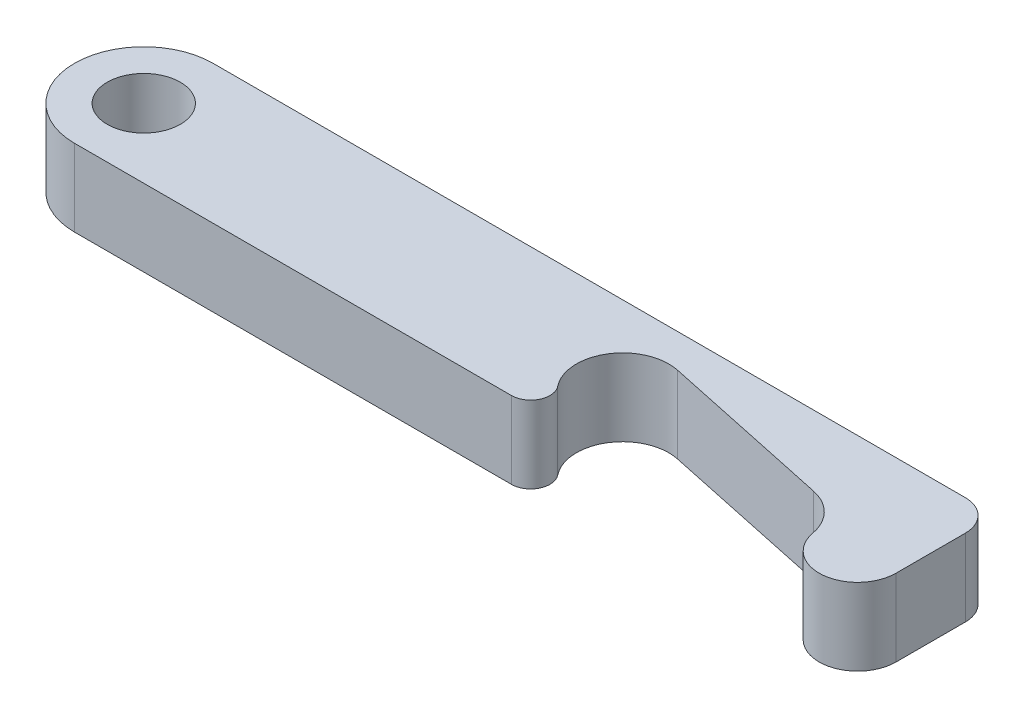
SolidWorks part; units mm, degrees
ref_plane "Front Plane" through (0, 0, 0) normal (0, 0, 1) x (1, 0, 0)
ref_plane "Top Plane" through (0, 0, 0) normal (0, 1, 0) x (1, 0, 0)
ref_plane "Right Plane" through (0, 0, 0) normal (1, 0, 0) x (0, 0, -1)
sketch "Sketch1" plane through (0, 0, 0) normal (0, 1, 0) x (1, 0, 0)
  line L0 (-50.5, 9) -> (47.2578, 9)
  line L1 (51.2578, 5) -> (51.2578, -4)
  line L2 (6.282, -9) -> (-50.5, -9)
  line L4 (14.1887, 4.6514) -> (36.6887, -0.1311)
  arc A0 (51.2578, 5) -> (47.2578, 9) centre (47.2578, 5) ccw
  arc A1 (46.2578, -9) -> (51.2578, -4) centre (46.2578, -4) ccw
  arc A2 (-50.5, 9) -> (-50.5, -9) centre (-50.5, 0) ccw
  circle A3 centre (-50.5, 0) radius 4.75
  arc A4 (14.1887, 4.6514) -> (8.2406, -4.9463) centre (12.9412, -1.2175) ccw
  arc A5 (41.3412, -4.9091) -> (36.6887, -0.1311) centre (35.4412, -6) ccw
  arc A6 (41.3412, -4.9091) -> (51.2578, -4) centre (46.2578, -4) ccw
  arc A7 (6.282, -9) -> (8.2406, -4.9463) centre (6.282, -6.5) ccw
  point P22 (-59.5, 0)
  dimension "D2" = 8
  dimension "D3" = 10
  dimension "D4" = 9.5
  dimension "D5" = 12
  dimension "D6" = 12
  dimension "D9" = 5
  dimension "D8" = 15
  dimension "D1" = 18
  dimension "D7" = 22.5
extrude "Boss-Extrude1" add sketch "Sketch1" along normal blind 10 contours L2 A7 A4 L4 A5 A6 A1 L1 A0 L0 A2 A3
